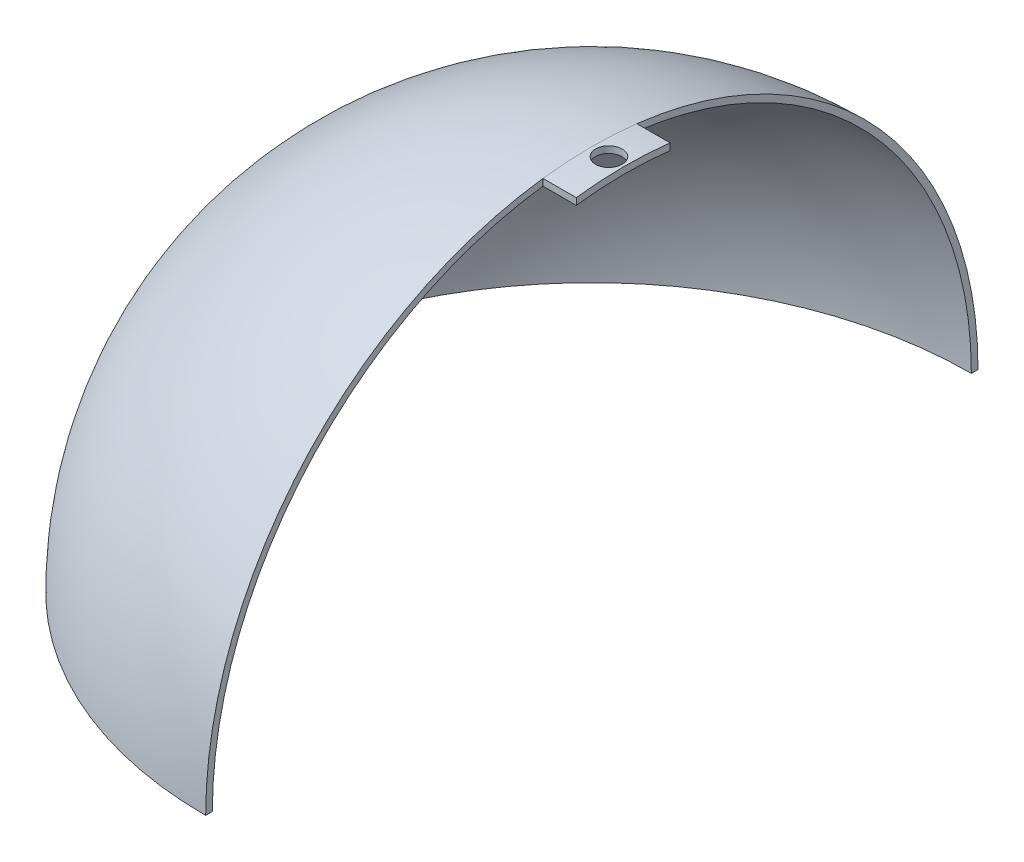
SolidWorks part; units mm, degrees
ref_plane "Front" through (0, 0, 0) normal (0, 0, 1) x (1, 0, 0)
ref_plane "Top" through (0, 0, 0) normal (0, 1, 0) x (1, 0, 0)
ref_plane "Right" through (0, 0, 0) normal (1, 0, 0) x (0, 0, -1)
sketch "Sketch1" plane through (0, 0, 0) normal (0, 1, 0) x (1, 0, 0)
  line L0 (0, 11600) -> (0, 11400)
  line L1 (0, -11400) -> (0, -11600)
  line L3 (0, -53.1644) -> (0, 55.1591) construction
  arc A0 (0, 11400) -> (0, -11400) centre (0, 0) ccw
  arc A1 (0, 11600) -> (0, -11600) centre (0, 0) ccw
revolve "Revolve1" add sketch "Sketch1" angle 90 about L3
ref_plane "Plane1" through (0, 11600, 0) normal (0, 1, 0) x (1, 0, 0)
sketch "Sketch3" plane through (0, 0, 0) normal (1, 0, 0) x (0, 0, -1)
  line L0 (-1467.8657, 11506.7532) -> (-1467.8657, 11305.1037)
  line L1 (1352.3028, 11319.5087) -> (1352.3028, 11520.9061)
  arc A0 (-1467.8657, 11305.1037) -> (1352.3028, 11319.5087) centre (0, 0) cw
  arc A1 (11400, 0) -> (-11400, 0) centre (0, 0) ccw construction
  arc A2 (-1467.8657, 11506.7532) -> (1352.3028, 11520.9061) centre (0, 0) cw
  arc A3 (11600, 0) -> (-11600, 0) centre (0, 0) ccw construction
extrude "Boss-Extrude1" add sketch "Sketch3" along normal blind 1000
sketch "Sketch4" plane through (0, 11600, 0) normal (0, 1, 0) x (1, 0, 0)
  line L0 (-6380, 0) -> (6380, 0) construction
  circle A0 centre (514.2933, 0) radius 400
extrude "Cut-Extrude1" cut sketch "Sketch4" against normal blind 1000
